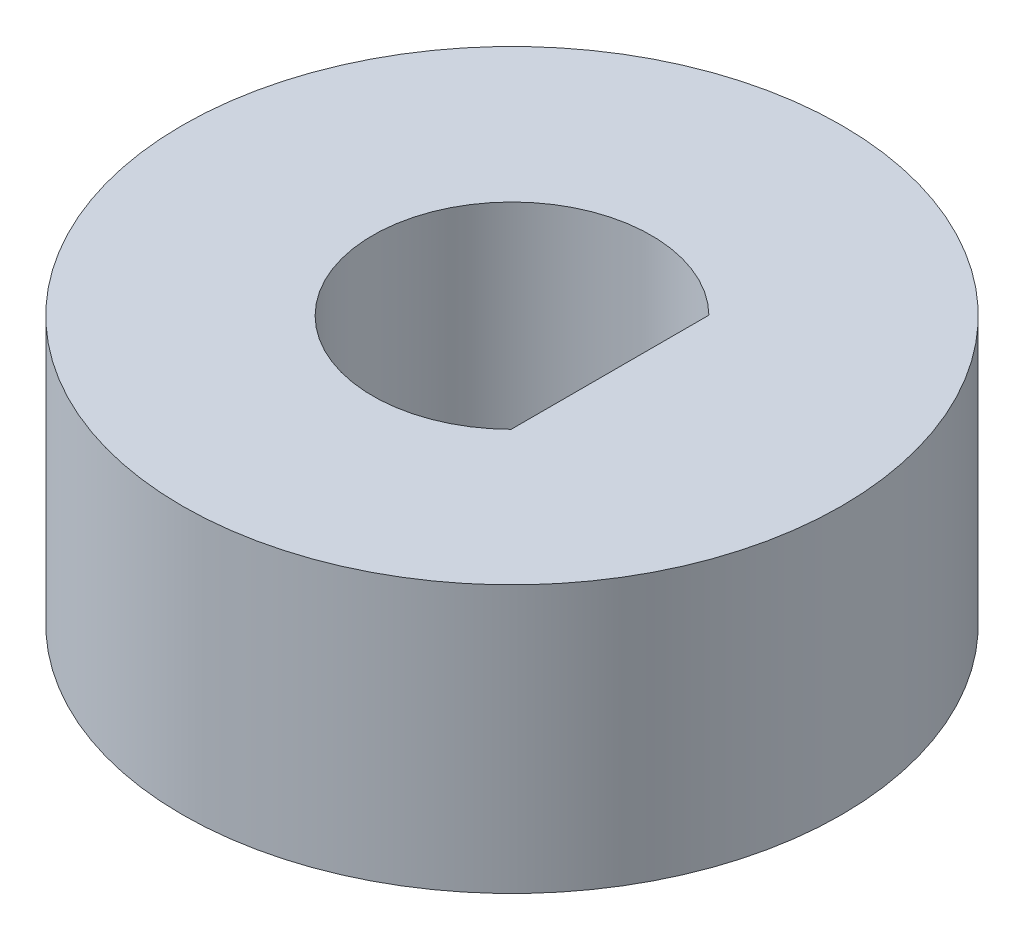
SolidWorks part; units mm, degrees
material "Custom Plastic"
ref_plane "Front Plane" through (0, 0, 0) normal (0, 0, 1) x (1, 0, 0)
ref_plane "Top Plane" through (0, 0, 0) normal (0, 1, 0) x (1, 0, 0)
ref_plane "Right Plane" through (0, 0, 0) normal (1, 0, 0) x (0, 0, -1)
sketch "Sketch1" plane through (0, 0, 0) normal (0, 1, 0) x (1, 0, 0)
  line L0 (2.2, 2.2194) -> (2.2, -2.2194)
  circle A0 centre (0, 0) radius 7.4
  arc A1 (2.2, 2.2194) -> (2.2, -2.2194) centre (0, 0) ccw
  dimension "D1" = 6.25
  dimension "D2" = 14.8
  dimension "D3" = 2.2
extrude "Boss-Extrude1" add sketch "Sketch1" along normal blind 6
